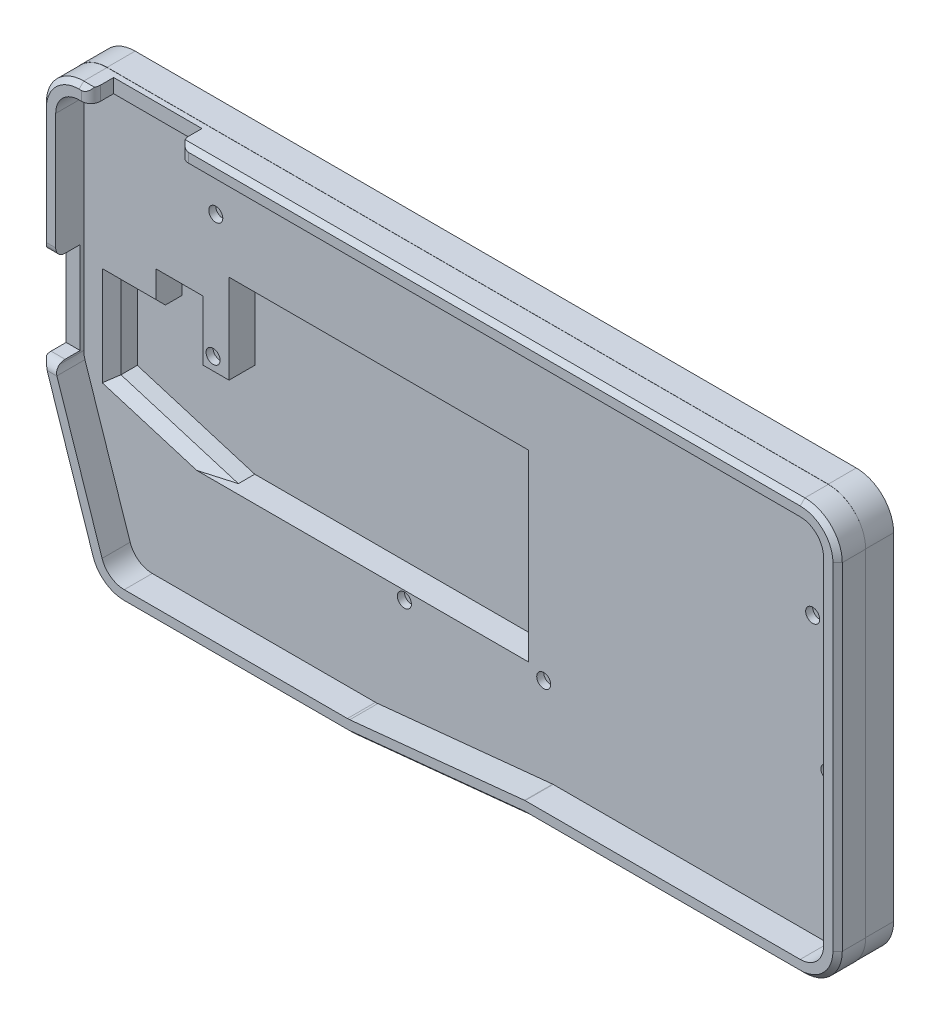
SolidWorks part; units mm, degrees
ref_plane "Front Plane" through (0, 0, 0) normal (0, 0, 1) x (1, 0, 0)
ref_plane "Top Plane" through (0, 0, 0) normal (0, 1, 0) x (1, 0, 0)
ref_plane "Right Plane" through (0, 0, 0) normal (1, 0, 0) x (0, 0, -1)
sketch "Sketch3" plane through (0, 0, 0) normal (0, 0, 1) x (1, 0, 0)
  line B0 (-83.6984, 57.4446) -> (70.5516, 57.3483)
  line B1 (78.5466, 49.3483) -> (78.5466, -22.6536)
  line B2 (70.5466, -30.6536) -> (11.7979, -30.6536)
  line B3 (11.7979, -30.6536) -> (-25.502, -34.4132)
  line B4 (-26.3043, -34.4536) -> (-74.0412, -34.4536)
  line B5 (-81.6306, -28.9834) -> (-91.2929, 0.0035)
  line B6 (-91.7034, 2.5333) -> (-91.7034, 49.4446)
  line B7 (-83.7003, 54.4446) -> (70.5497, 54.3483)
  line B8 (75.5466, 49.3483) -> (75.5466, -22.6536)
  line B9 (70.5466, -27.6536) -> (11.6974, -27.6536)
  line B10 (11.5971, -27.6586) -> (-25.8028, -31.4283)
  line B11 (-26.3043, -31.4536) -> (-74.0412, -31.4536)
  line B12 (-78.7846, -28.0347) -> (-88.4469, 0.9521)
  line B13 (-88.7034, 2.5333) -> (-88.7034, 49.4446)
  arc B14 (78.5466, 49.3483) -> (70.5516, 57.3483) centre (70.5466, 49.3483) ccw
  arc B15 (70.5466, -30.6536) -> (78.5466, -22.6536) centre (70.5466, -22.6536) ccw
  arc B16 (-26.3043, -34.4536) -> (-25.502, -34.4132) centre (-26.3043, -26.4536) ccw
  arc B17 (-81.6306, -28.9834) -> (-74.0412, -34.4536) centre (-74.0412, -26.4536) ccw
  arc B18 (-91.7034, 2.5333) -> (-91.2929, 0.0035) centre (-83.7034, 2.5333) ccw
  arc B19 (-83.6984, 57.4446) -> (-91.7034, 49.4446) centre (-83.7034, 49.4446) ccw
  arc B20 (75.5466, 49.3483) -> (70.5497, 54.3483) centre (70.5466, 49.3483) ccw
  arc B21 (70.5466, -27.6536) -> (75.5466, -22.6536) centre (70.5466, -22.6536) ccw
  arc B22 (11.6974, -27.6536) -> (11.5971, -27.6586) centre (11.6974, -28.6536) ccw
  arc B23 (-26.3043, -31.4536) -> (-25.8028, -31.4283) centre (-26.3043, -26.4536) ccw
  arc B24 (-78.7846, -28.0347) -> (-74.0412, -31.4536) centre (-74.0412, -26.4536) ccw
  arc B25 (-88.7034, 2.5333) -> (-88.4469, 0.9521) centre (-83.7034, 2.5333) ccw
  arc B26 (-83.7003, 54.4446) -> (-88.7034, 49.4446) centre (-83.7034, 49.4446) ccw
sketch_block_instance "wall_outline (2)-1"
sketch_block "wall_outline (2)"
extrude "Boss-Extrude1" add sketch "Sketch3" along normal blind 6
sketch "Sketch4" plane through (0, 0, 0) normal (0, 0, 1) x (1, 0, 0)
  line B0 (-83.7091, 57.4792) -> (70.5409, 57.3829)
  line B1 (78.5359, 49.3829) -> (78.5359, -22.619)
  line B2 (70.5359, -30.619) -> (11.7872, -30.619)
  line B3 (11.7872, -30.619) -> (-25.5126, -34.3786)
  line B4 (-26.3149, -34.419) -> (-74.0518, -34.419)
  line B5 (-81.6413, -28.9488) -> (-91.3036, 0.038)
  line B6 (-91.7141, 2.5679) -> (-91.7141, 49.4792)
  line B7 (-83.711, 54.4792) -> (70.539, 54.3829)
  line B8 (75.5359, 49.3829) -> (75.5359, -22.619)
  line B9 (70.5359, -27.619) -> (11.6867, -27.619)
  line B10 (11.5864, -27.624) -> (-25.8135, -31.3938)
  line B11 (-26.3149, -31.419) -> (-74.0518, -31.419)
  line B12 (-78.7953, -28.0001) -> (-88.4575, 0.9867)
  line B13 (-88.7141, 2.5679) -> (-88.7141, 49.4792)
  arc B14 (78.5359, 49.3829) -> (70.5409, 57.3829) centre (70.5359, 49.3829) ccw
  arc B15 (70.5359, -30.619) -> (78.5359, -22.619) centre (70.5359, -22.619) ccw
  arc B16 (-26.3149, -34.419) -> (-25.5126, -34.3786) centre (-26.3149, -26.419) ccw
  arc B17 (-81.6413, -28.9488) -> (-74.0518, -34.419) centre (-74.0518, -26.419) ccw
  arc B18 (-91.7141, 2.5679) -> (-91.3036, 0.038) centre (-83.7141, 2.5679) ccw
  arc B19 (-83.7091, 57.4792) -> (-91.7141, 49.4792) centre (-83.7141, 49.4792) ccw
  arc B20 (75.5359, 49.3829) -> (70.539, 54.3829) centre (70.5359, 49.3829) ccw
  arc B21 (70.5359, -27.619) -> (75.5359, -22.619) centre (70.5359, -22.619) ccw
  arc B22 (11.6867, -27.619) -> (11.5864, -27.624) centre (11.6867, -28.619) ccw
  arc B23 (-26.3149, -31.419) -> (-25.8135, -31.3938) centre (-26.3149, -26.419) ccw
  arc B24 (-78.7953, -28.0001) -> (-74.0518, -31.419) centre (-74.0518, -26.419) ccw
  arc B25 (-88.7141, 2.5679) -> (-88.4575, 0.9867) centre (-83.7141, 2.5679) ccw
  arc B26 (-83.711, 54.4792) -> (-88.7141, 49.4792) centre (-83.7141, 49.4792) ccw
  circle B27 centre (-60.4641, 41.881) radius 1
  circle B28 centre (-61.0341, 15.281) radius 1
  circle B29 centre (-20.1141, -9.419) radius 1
  circle B30 centre (9.6859, -9.419) radius 1
  circle B31 centre (70.4859, 3.881) radius 1
  circle B32 centre (67.2159, 31.431) radius 1
sketch_block_instance "wall_outline (3)-1"
sketch_block "wall_outline (3)"
extrude "Boss-Extrude2" add sketch "Sketch4" against normal blind 6 contours B7 B26 B13 B25 B12 B24 B11 B23 B10 B22 B9 B21 B8 B20 B32 B31 B30 B29 B28 B27 | B0 B19 B6 B18 B5 B17 B4 B16 B3 B2 B15 B1 B14 B26 B7 B20 B8 B21 B9 B22 B10 B23 B11 B24 B12 B25 B13
sketch "Sketch5" plane through (0, 0, 0) normal (0, 0, 1) x (1, 0, 0)
  line L1 (-57.625, 35.0163) -> (6.3958, 35.0163)
  line L2 (-57.625, 35.0163) -> (-57.625, -7.6057)
  line L3 (-57.625, -7.6057) -> (6.3958, -7.6057)
  line L4 (6.3958, 35.0163) -> (6.3958, -7.6057)
  line L5 (-76.0419, 12.5652) -> (-50.0828, 12.5652)
  line L6 (-76.0419, 12.5652) -> (-76.0419, -1.6421)
  line L7 (-76.0419, -1.6421) -> (-50.0828, -1.6421)
  line L8 (-50.0828, 12.5652) -> (-50.0828, -1.6421)
extrude "Cut-Extrude2" cut sketch "Sketch5" against normal blind 5.5 contours L6 L7 L2 L5 | L8 L5 L2 L7 | L5 L8 L7 L2 L3 L4 L1
sketch "Sketch6" plane through (0, 0, -6) normal (0, 0, -1) x (-1, 0, 0)
  circle A0 centre (-67.2159, 31.431) radius 1
  circle A1 centre (-70.4859, 3.881) radius 1
  circle A2 centre (-9.6859, -9.419) radius 1
  circle A3 centre (20.1141, -9.419) radius 1
  circle A4 centre (61.0341, 15.281) radius 1
  circle A5 centre (60.4641, 41.881) radius 1
extrude "Boss-Extrude3" add sketch "Sketch6" against normal blind 5.5
sketch "Sketch7" plane through (0, 0, 0) normal (0, 0, 1) x (1, 0, 0)
  circle A0 centre (-60.4641, 41.881) radius 1.5
  circle A1 centre (-61.0341, 15.281) radius 1.5
  circle A2 centre (-20.1141, -9.419) radius 1.5
  circle A3 centre (9.6859, -9.419) radius 1.5
  circle A7 centre (70.4859, 3.881) radius 1.5
  circle A8 centre (67.2159, 31.431) radius 1.5
extrude "Cut-Extrude3" cut sketch "Sketch7" against normal blind 1.5
sketch "Sketch8" plane through (0, 0, -6) normal (0, 0, -1) x (-1, 0, 0)
  line L0 (-70.5359, 49.3829) -> (-70.5359, -22.1639)
  line L1 (-70.5359, 49.3829) -> (83.7595, 49.3829)
  line L2 (-70.5359, -22.1639) -> (73.5863, -25.6718)
  circle A0 centre (-70.5359, 49.3829) radius 6
  circle A1 centre (-70.5359, -22.1639) radius 6
  circle A2 centre (83.7595, 49.3829) radius 6
  circle A3 centre (73.5863, -25.6718) radius 6
extrude "Cut-Extrude4" cut sketch "Sketch8" against normal blind 2.5
chamfer "Chamfer1" distance 1 angle 45 13 edges at (-78.7188, -32.9435, 6) (-86.4618, -14.49, 6) (-91.6001, 1.2518, 6) (-91.7034, 25.9889, 6) (-89.3585, 55.1032, 6) (-6.5734, 57.3964, 6) (76.2052, 55.0034, 6) (78.5466, 13.3474, 6) (76.2034, -28.3104, 6) (41.1722, -30.6536, 6) (-6.852, -32.5334, 6) (-25.9026, -34.4435, 6) (-50.1727, -34.4536, 6)
sketch "Sketch9" plane through (0.0358, 57.3923, 0) normal (0.0006, 1, 0) x (1, -0.0006, 0)
  line L1 (-81.193, -1.1526) -> (-62.3001, -1.1526)
  line L2 (-81.193, -1.1526) -> (-81.193, -7.0139)
  line L3 (-81.193, -7.0139) -> (-62.3001, -7.0139)
  line L4 (-62.3001, -1.1526) -> (-62.3001, -7.0139)
extrude "Cut-Extrude5" cut sketch "Sketch9" against normal blind 5
fillet "Fillet1" radius 2 2 edges at (-62.2655, 55.4312, 6) (-81.1584, 55.443, 6)
sketch "Sketch10" plane through (-91.7034, 0, 0) normal (-1, 0, 0) x (0, 0, 1)
  line L1 (0.7673, 22.5231) -> (7.5488, 22.5231)
  line L2 (0.7673, 22.5231) -> (0.7673, 2.8993)
  line L3 (0.7673, 2.8993) -> (7.5488, 2.8993)
  line L4 (7.5488, 22.5231) -> (7.5488, 2.8993)
extrude "Cut-Extrude6" cut sketch "Sketch10" against normal blind 5
fillet "Fillet2" radius 2 2 edges at (-89.7034, 2.8993, 6) (-89.7034, 22.5231, 6)
sketch "Sketch11" plane through (0, 0, 0) normal (0, 0, 1) x (1, 0, 0)
  line L1 (-73.2355, 25.3693) -> (-63.2377, 25.3693)
  line L2 (-73.2355, 25.3693) -> (-73.2355, 9.408)
  line L3 (-73.2355, 9.408) -> (-63.2377, 9.408)
  line L4 (-63.2377, 25.3693) -> (-63.2377, 9.408)
extrude "Cut-Extrude7" cut sketch "Sketch11" against normal blind 5.5
sketch "Sketch12" plane through (0, 0, -5.5) normal (0, 0, 1) x (1, 0, 0)
  line L0 (6.3958, 35.0163) -> (6.3958, -7.6057) construction
  line L1 (-57.625, 35.0163) -> (6.3958, 35.0163)
  line L2 (-57.625, 35.0163) -> (-57.625, 31.6402)
  line L3 (-57.625, 31.6402) -> (6.3958, 31.6402)
  line L4 (6.3958, 35.0163) -> (6.3958, 31.6402)
extrude "Boss-Extrude4" add sketch "Sketch12" along normal blind 5.5
sketch "Sketch13" plane through (0, 0, 0) normal (0, 0, 1) x (1, 0, 0)
  line L0 (-82.7449, 0) -> (-57.625, -7.6057)
  line L1 (-57.625, -7.6057) -> (-82.7449, 0)
  line L2 (-82.7449, 0) -> (-82.7449, 17.6789)
  line L3 (-82.7449, 17.6789) -> (-68.4274, 17.6789)
  line L4 (-68.4274, 17.6789) -> (-51.1131, -1.3002)
  line L5 (-51.1131, -1.3002) -> (-57.625, -7.6057)
  line M5 (-57.625, -7.6057) -> (-57.625, -1.6421)
  line M6 (-57.625, -1.6421) -> (-76.0419, -1.6421)
  line M7 (-76.0419, -1.6421) -> (-76.0419, 12.5652)
  line M8 (-76.0419, 12.5652) -> (-73.2355, 12.5652)
  line M9 (-73.2355, 12.5652) -> (-73.2355, 25.3693)
extrude "Cut-Extrude8" cut sketch "Sketch13" against normal blind 5.5 contours L3 L2 L0 M5 M6 M7 M8 M9
chamfer "Chamfer2" distance 2 angle 45 1 edges at (-82.7449, 8.8394, 0)
chamfer "Chamfer3" distance 2 angle 45 1 edges at (-78.9902, 17.6789, 0)
chamfer "Chamfer4" distance 2 angle 45 1 edges at (-71.1849, -3.5001, 0)
